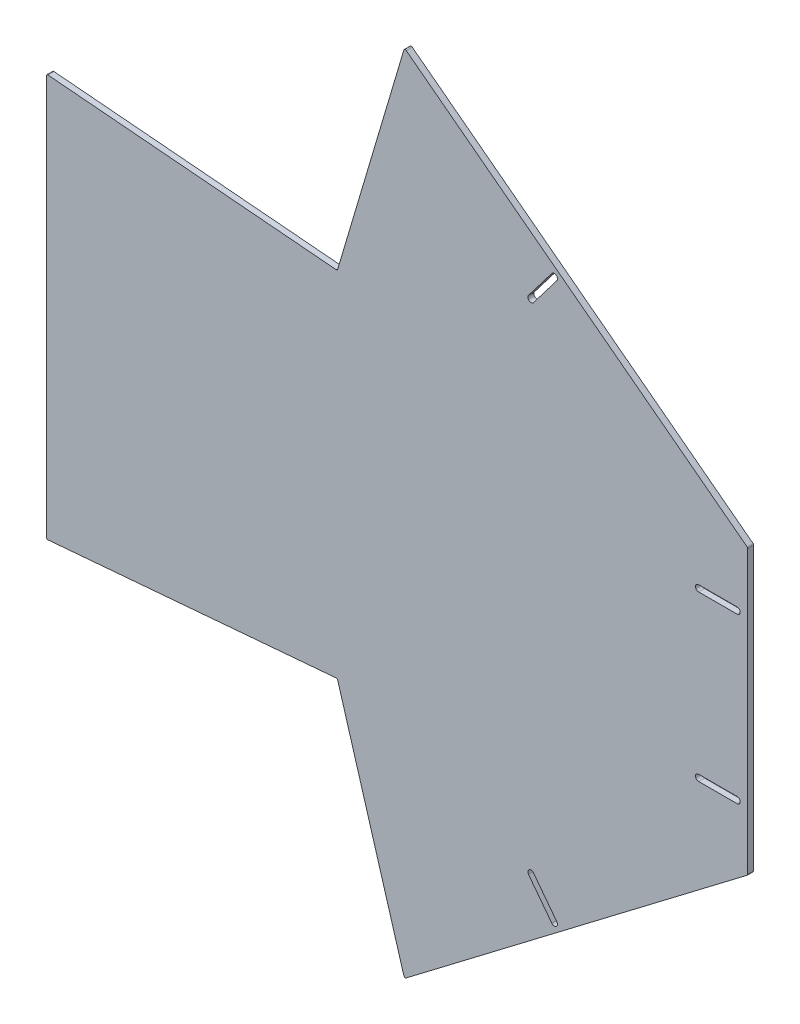
SolidWorks part; units mm, degrees
ref_plane "Front Plane" through (0, 0, 0) normal (1, 0, 0) x (0, 1, 0)
ref_plane "Top Plane" through (0, 0, 0) normal (0, 0, 1) x (0, 1, 0)
ref_plane "Right Plane" through (0, 0, 0) normal (0, 1, 0) x (-1, 0, 0)
sketch "Sketch1" plane through (0, 0, 0) normal (0, 0, 1) x (0, 1, 0)
  line L0 (0, 0) -> (190, 0)
  line L1 (190, 0) -> (230, 470)
  line L2 (230, 470) -> (-40, 470)
  line L3 (-40, 470) -> (0, 0)
  line L4 (-175, 230) -> (-23.4043, 275)
  line L5 (-175, 230) -> (0, 0)
  line L7 (0, 0) -> (190, 0)
  line L9 (-23.4043, 275) -> (0, 0)
  line L11 (95, -5.3645) -> (95, 67.5736) construction
  line L12 (213.4043, 275) -> (190, 0)
  line L13 (365, 230) -> (213.4043, 275)
  line L14 (365, 230) -> (190, 0)
  line L15 (-175, 230) -> (-175, 322.6075) construction
  line L16 (-92.303, 129.5699) -> (-71.7706, 145.1923) construction
  line L17 (-93.5746, 131.2411) -> (-73.0422, 146.8636)
  line L18 (-91.0314, 127.8986) -> (-70.499, 143.5211)
  line L19 (40, 32.9) -> (40, 7.1) construction
  line L20 (42.1, 32.9) -> (42.1, 7.1)
  line L21 (37.9, 32.9) -> (37.9, 7.1)
  line L22 (150, 32.9) -> (150, 7.1) construction
  line L23 (147.9, 32.9) -> (147.9, 7.1)
  line L24 (152.1, 32.9) -> (152.1, 7.1)
  line L25 (282.303, 129.5699) -> (261.7706, 145.1923) construction
  line L26 (283.5746, 131.2411) -> (263.0422, 146.8636)
  line L27 (281.0314, 127.8986) -> (260.499, 143.5211)
  arc A0 (-93.5746, 131.2411) -> (-91.0314, 127.8986) centre (-92.303, 129.5699) ccw
  arc A1 (-70.499, 143.5211) -> (-73.0422, 146.8636) centre (-71.7706, 145.1923) ccw
  arc A2 (42.1, 32.9) -> (37.9, 32.9) centre (40, 32.9) ccw
  arc A3 (37.9, 7.1) -> (42.1, 7.1) centre (40, 7.1) ccw
  arc A4 (147.9, 32.9) -> (152.1, 32.9) centre (150, 32.9) cw
  arc A5 (152.1, 7.1) -> (147.9, 7.1) centre (150, 7.1) cw
  arc A6 (283.5746, 131.2411) -> (281.0314, 127.8986) centre (282.303, 129.5699) cw
  arc A7 (260.499, 143.5211) -> (263.0422, 146.8636) centre (261.7706, 145.1923) cw
  point P3 (95, 470)
  point P6 (95, 0)
  point P7 (-82.0368, 137.3811)
  point P21 (-93.9743, 128.2983)
  point P22 (40, 20)
  point P34 (150, 20)
  point P41 (272.0368, 137.3811)
  dimension "D8" = 30
  dimension "D13" = 30
  dimension "D15" = 5
  dimension "D1" = 270
  dimension "D2" = 190
  dimension "D3" = 470
  dimension "D4" = 275
  dimension "D5" = 230
  dimension "D6" = 175
  dimension "D7" = 158.1337
  dimension "D9" = 4.2
  dimension "D10" = 130
  dimension "D11" = 5
  dimension "D12" = 4.2
  dimension "D14" = 40
extrude "Boss-Extrude1" add sketch "Sketch1" along normal blind 4
fillet "Fillet1" radius 1 8 edges at (-275, -23.4043, 2) (-470, -40, 2) (-470, 230, 2) (0, 190, 2) (0, 0, 2) (-230, -175, 2) (-275, 213.4043, 2) (-230, 365, 2)
